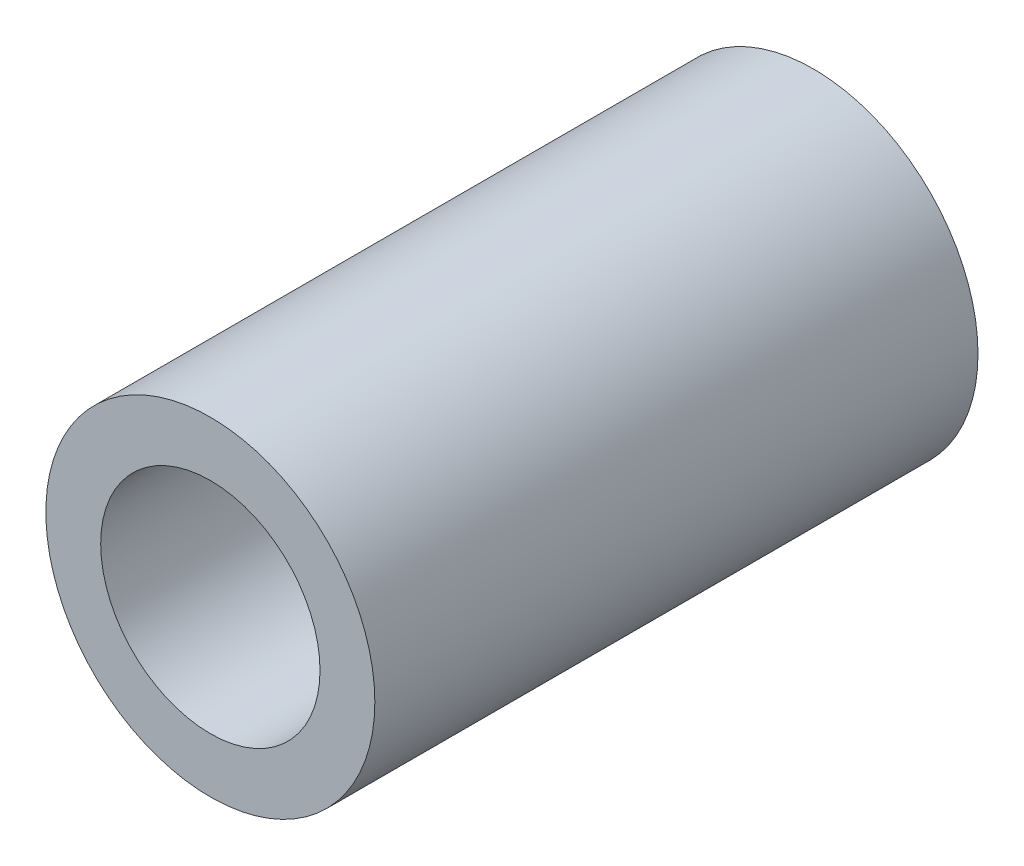
SolidWorks part; units mm, degrees
other "Bearing_3-1-1"
material "PTFE (general)"
ref_plane "Front" through (0, 0, 0) normal (0, 0, 1) x (1, 0, 0)
ref_plane "Top" through (0, 0, 0) normal (0, 1, 0) x (1, 0, 0)
ref_plane "Right" through (0, 0, 0) normal (1, 0, 0) x (0, 0, -1)
sketch "BearingSke" plane through (0, 0, 0) normal (0, 0, 1) x (1, 0, 0)
  circle A0 centre (0, 0) radius 1.5
  circle A1 centre (0, 0) radius 1
  dimension "D1" = 3
  dimension "D2" = 2
extrude "Bearing" add sketch "BearingSke" along normal blind 5.5
